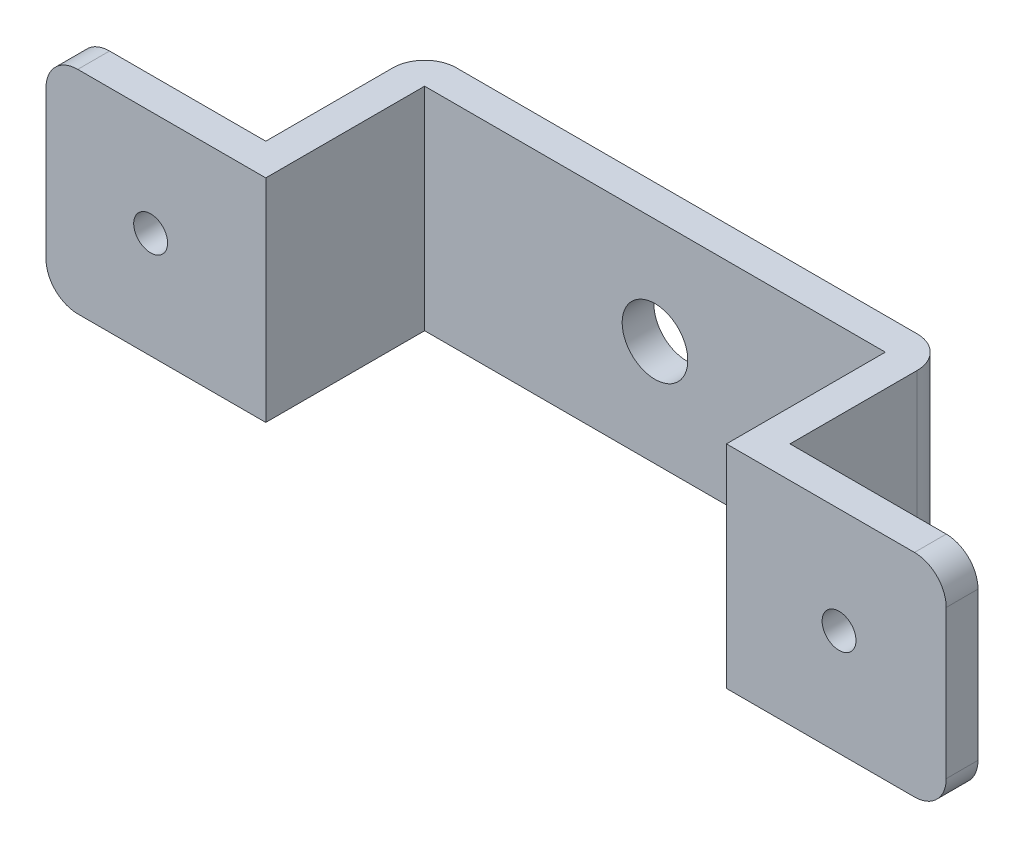
SolidWorks part; units mm, degrees
ref_plane "Front Plane" through (0, 0, 0) normal (0, 0, 1) x (1, 0, 0)
ref_plane "Top Plane" through (0, 0, 0) normal (0, 1, 0) x (1, 0, 0)
ref_plane "Right Plane" through (0, 0, 0) normal (1, 0, 0) x (0, 0, -1)
sketch "Sketch1" plane through (0, 0, 0) normal (0, 0, 1) x (1, 0, 0)
  line L1 (-42.5, -10) -> (42.5, -10)
  line L2 (-42.5, -10) -> (-42.5, 10)
  line L3 (-42.5, 10) -> (42.5, 10)
  line L4 (42.5, -10) -> (42.5, 10)
  line L5 (-42.5, -10) -> (42.5, 10) construction
  line L6 (-42.5, 10) -> (42.5, -10) construction
  point P0 (0, 0)
extrude "Boss-Extrude1" add sketch "Sketch1" along normal blind 3
sketch "Sketch2" plane through (0, 0, 0) normal (0, 0, -1) x (-1, 0, 0)
  line L0 (-42.5, 10) -> (42.5, 10) construction
  line L2 (21.75, -10) -> (21.75, 10)
  line L4 (-21.75, -10) -> (-21.75, 10)
  line L7 (42.5, -10) -> (-42.5, -10) construction
  line L8 (-21.75, 10) -> (-24.75, 10)
  line L9 (-21.75, 10) -> (-21.75, -10)
  line L10 (-21.75, -10) -> (-24.75, -10)
  line L11 (-24.75, 10) -> (-24.75, -10)
  line L13 (21.75, 10) -> (24.75, 10)
  line L14 (21.75, 10) -> (21.75, -10)
  line L15 (21.75, -10) -> (24.75, -10)
  line L16 (24.75, 10) -> (24.75, -10)
  point P0 (0, 0)
  line M6 (-42.5, -10) -> (42.5, -10)
  line M8 (42.5, 10) -> (-42.5, 10)
extrude "Boss-Extrude2" add sketch "Sketch2" along normal blind 12 contours L11 L4 M8 M6 | L16 L2 M8 M6
sketch "Sketch3" plane through (0, 0, -12) normal (0, 0, -1) x (-1, 0, 0)
  line L1 (-24.75, 10) -> (24.75, 10)
  line L2 (-24.75, 10) -> (-24.75, -10)
  line L3 (-24.75, -10) -> (24.75, -10)
  line L4 (24.75, 10) -> (24.75, -10)
extrude "Boss-Extrude3" add sketch "Sketch3" along normal blind 3
sketch "Sketch4" plane through (0, -10, 0) normal (0, -1, 0) x (1, 0, 0)
  line L0 (-42.5, 3) -> (42.5, 3) construction
  line L1 (-21.75, 0) -> (21.75, 0)
  line L2 (-21.75, 0) -> (-21.75, 3)
  line L3 (-21.75, 3) -> (21.75, 3)
  line L4 (21.75, 0) -> (21.75, 3)
extrude "Cut-Extrude1" cut sketch "Sketch4" against normal through all
sketch "Sketch5" plane through (0, 0, -15) normal (0, 0, -1) x (-1, 0, 0)
  circle A0 centre (0, 0) radius 3.1
extrude "Cut-Extrude2" cut sketch "Sketch5" against normal through all
sketch "Sketch6" plane through (0, 0, 3) normal (0, 0, 1) x (1, 0, 0)
  circle A0 centre (32.3806, 0.031) radius 1.6
  circle A1 centre (-32.6194, 0.031) radius 1.6
extrude "Cut-Extrude3" cut sketch "Sketch6" against normal through all
fillet "Fillet1" radius 3 6 edges at (-24.75, 0, -15) (24.75, 0, -15) (42.5, -10, 1.5) (42.5, 10, 1.5) (-42.5, -10, 1.5) (-42.5, 10, 1.5)
